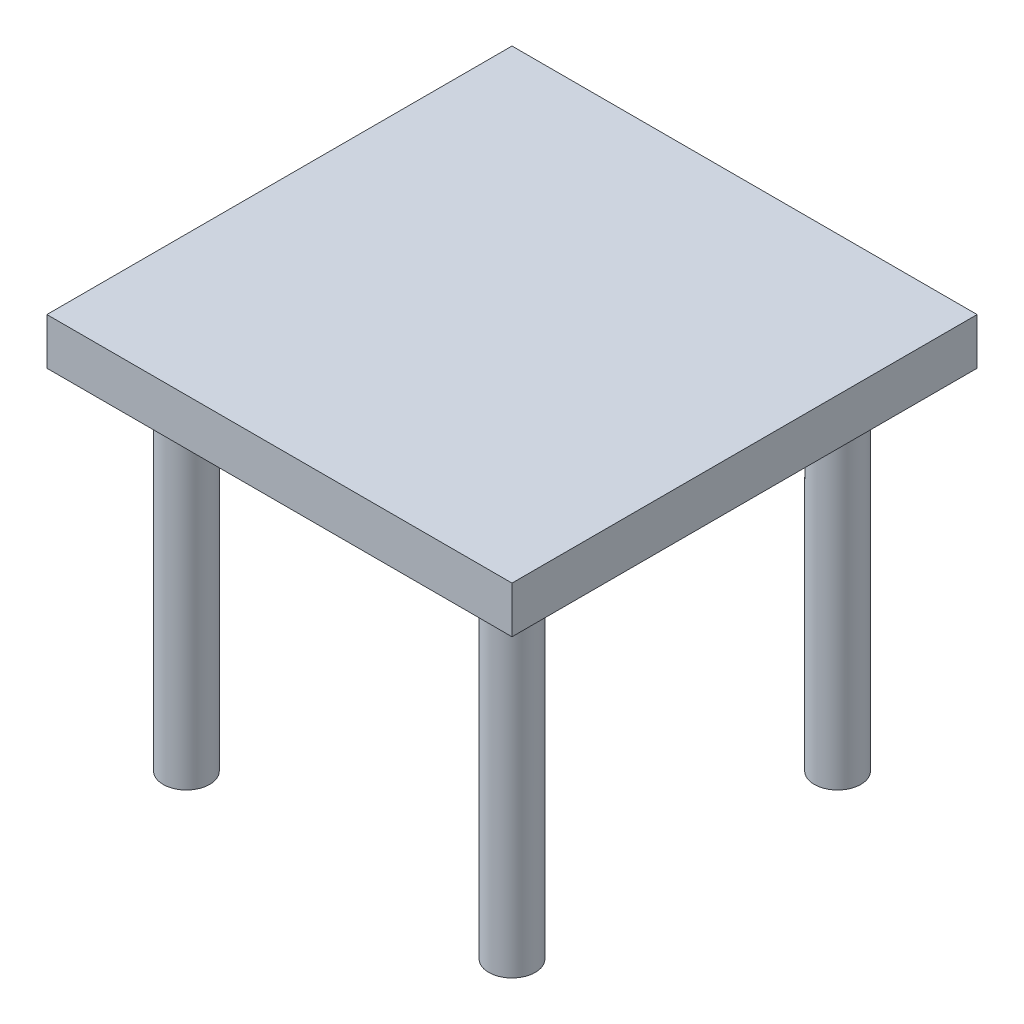
SolidWorks part; units mm, degrees
ref_plane "前视基准面" through (0, 0, 0) normal (0, 0, 1) x (1, 0, 0)
ref_plane "上视基准面" through (0, 0, 0) normal (0, 1, 0) x (1, 0, 0)
ref_plane "右视基准面" through (0, 0, 0) normal (1, 0, 0) x (0, 0, -1)
ref_plane "基准面1" through (0, 150, 0) normal (0, 1, 0) x (1, 0, 0)
sketch "草图1" plane through (0, 150, 0) normal (0, 1, 0) x (1, 0, 0)
  line L0 (-100, 100) -> (100, 100)
  line L1 (100, 100) -> (100, -100)
  line L2 (100, -100) -> (-100, -100)
  line L3 (-100, -100) -> (-100, 100)
extrude "凸台-拉伸1" add sketch "草图1" along normal blind 20
ref_plane "基准面2" through (0, 152, 0) normal (0, 1, 0) x (1, 0, 0)
sketch "草图2" plane through (0, 152, 0) normal (0, 1, 0) x (1, 0, 0)
  circle A0 centre (-70, 70) radius 10
  circle A1 centre (70, 70) radius 10
  circle A2 centre (-70, -70) radius 10
  circle A3 centre (70, -70) radius 10
extrude "凸台-拉伸2" add sketch "草图2" against normal blind 152
